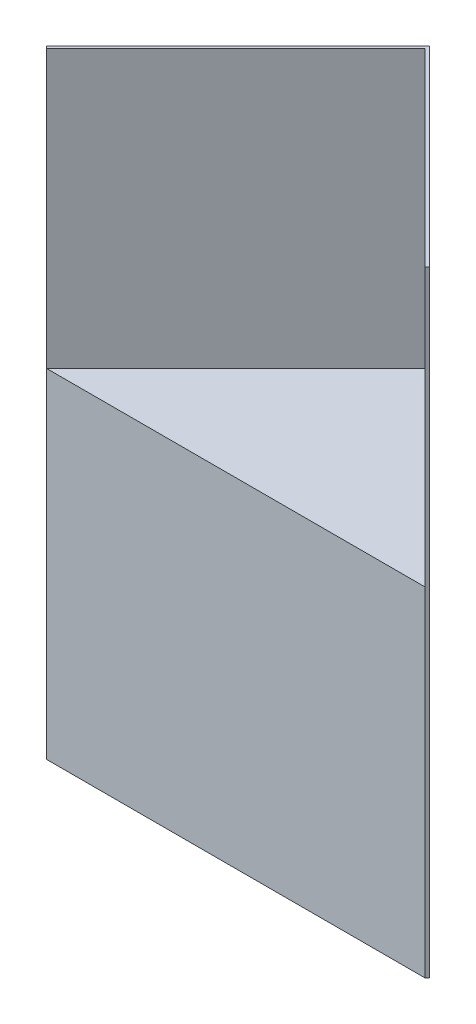
SolidWorks part; units mm, degrees
ref_plane "Front" through (0, 0, 0) normal (0, 0, 1) x (1, 0, 0)
ref_plane "Top" through (0, 0, 0) normal (0, 1, 0) x (1, 0, 0)
ref_plane "Right" through (0, 0, 0) normal (1, 0, 0) x (0, 0, -1)
sketch "Sketch2" plane through (0, 0, 0) normal (0, 1, 0) x (1, 0, 0)
  line L0 (0, 0) -> (-781.05, -781.05)
  line L1 (-781.05, -781.05) -> (781.05, -781.05)
  line L2 (781.05, -781.05) -> (0, 0)
  dimension "D1" = 1562.1
extrude "Boss-Extrude1" add sketch "Sketch2" along normal blind 1397
sketch "Sketch3" plane through (0, 0, 0) normal (0, 1, 0) x (1, 0, 0)
  line L0 (790.0303, -772.0697) -> (0, 17.9605)
  line L1 (0, 17.9605) -> (-790.0303, -772.0697)
  line L2 (781.05, -781.05) -> (790.0303, -772.0697)
  line L3 (781.05, -781.05) -> (0, 0)
  line L4 (0, 0) -> (-781.05, -781.05)
  line L5 (-781.05, -781.05) -> (781.05, -781.05)
  line L6 (781.05, -781.05) -> (0, 0)
  line L7 (0, 0) -> (-781.05, -781.05)
  line L8 (-781.05, -781.05) -> (-790.0303, -772.0697)
  dimension "D1" = 0
  dimension "D2" = 12.7
extrude "Boss-Extrude2" add sketch "Sketch3" along normal blind 2540
